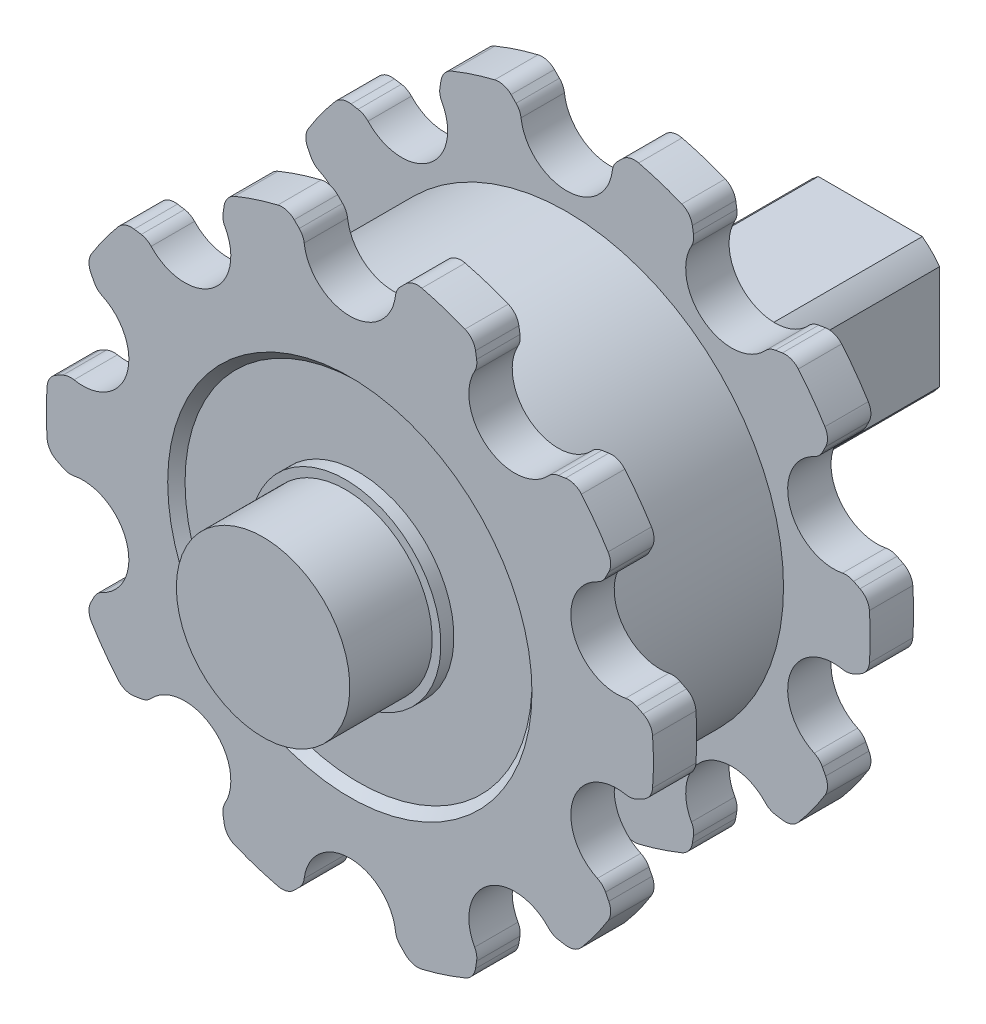
SolidWorks part; units mm, degrees
material "ABS"
ref_plane "Piano frontale" through (0, 0, 0) normal (0, 0, 1) x (1, 0, 0)
ref_plane "Piano superiore" through (0, 0, 0) normal (0, 1, 0) x (1, 0, 0)
ref_plane "Piano destro" through (0, 0, 0) normal (1, 0, 0) x (0, 0, -1)
sketch "Schizzo1" plane through (0, 0, 0) normal (0, 1, 0) x (1, 0, 0)
  line L0 (0, 0) -> (10, 0)
  line L1 (10, 0) -> (10, 9.5)
  line L2 (10, 9.5) -> (11, 9.5)
  line L3 (11, 9.5) -> (11, 11)
  line L4 (11, 11) -> (20, 11)
  line L5 (20, 11) -> (21, 10)
  line L6 (21, 10) -> (35, 10)
  line L7 (35, 10) -> (35, 15)
  line L8 (35, 15) -> (25, 15)
  line L9 (25, 15) -> (25, 35)
  line L10 (25, 35) -> (35, 35)
  line L11 (35, 35) -> (35, 40)
  line L12 (35, 40) -> (21, 40)
  line L13 (21, 40) -> (20, 39)
  line L14 (20, 39) -> (11, 39)
  line L15 (11, 39) -> (11, 40.5)
  line L16 (11, 40.5) -> (10, 40.5)
  line L17 (10, 40.5) -> (10, 70)
  line L20 (10, 70) -> (0, 70)
  line L21 (0, 70) -> (0, 0)
  dimension "D1" = 9.5
  dimension "D2" = 1
  dimension "D3" = 1.5
  dimension "D4" = 9
  dimension "D5" = 1
  dimension "D6" = 1
  dimension "D7" = 14
  dimension "D8" = 5
  dimension "D9" = 20
  dimension "D10" = 10
  dimension "D11" = 15
  dimension "D12" = 29.5
revolve "Rivoluzione1" add sketch "Schizzo1" angle 360 about L21
sketch "Schizzo2" plane through (0, 0, -70) normal (0, 0, -1) x (-1, 0, 0)
  line L0 (-8, -6) -> (-8, 6)
  line L1 (8, -6) -> (8, 6)
  line L2 (-6, 8) -> (6, 8)
  line L3 (-6, -8) -> (6, -8)
  arc A0 (6, 8) -> (-6, 8) centre (0, 0) ccw
  arc A1 (8, -6) -> (8, 6) centre (0, 0) ccw
  arc A2 (-8, 6) -> (-8, -6) centre (0, 0) ccw
  arc A3 (-6, -8) -> (6, -8) centre (0, 0) ccw
  dimension "D2" = 20
  dimension "D1" = 12
extrude "Taglio-Estrusione1" cut sketch "Schizzo2" against normal blind 20
sketch "Schizzo3" plane through (0, 0, -40) normal (0, 0, -1) x (-1, 0, 0)
  line L0 (0, 32.3607) -> (0, 27.0607) construction
  line L1 (0, 27.0607) -> (0, 0) construction
  line L2 (-5.8323, 32.893) -> (-6.4121, 33.4727)
  line L3 (-5.3, 32.3607) -> (0, 32.3607) construction
  line L4 (5.8323, 32.893) -> (6.4121, 33.4727)
  line L5 (0, 32.3607) -> (5.3, 32.3607) construction
  line L6 (14.6156, 30.0391) -> (14.4873, 30.8489)
  line L7 (24.0525, 23.1828) -> (24.8623, 23.3111)
  line L8 (19.0211, 26.1803) -> (15.9059, 21.8925) construction
  line L9 (15.9059, 21.8925) -> (0, 0) construction
  line L10 (14.7333, 29.2956) -> (19.0211, 26.1803) construction
  line L11 (19.0211, 26.1803) -> (23.3089, 23.0651) construction
  line L12 (29.4808, 15.7114) -> (29.853, 16.4419)
  line L13 (33.0854, 4.6176) -> (33.8159, 4.2454)
  line L14 (30.7768, 10) -> (25.7362, 8.3622) construction
  line L15 (25.7362, 8.3622) -> (0, 0) construction
  line L16 (29.139, 15.0406) -> (30.7768, 10) construction
  line L17 (30.7768, 10) -> (32.4146, 4.9594) construction
  line L18 (33.0854, -4.6176) -> (33.8159, -4.2454)
  line L19 (29.4808, -15.7114) -> (29.853, -16.4419)
  line L20 (30.7768, -10) -> (25.7362, -8.3622) construction
  line L21 (25.7362, -8.3622) -> (0, 0) construction
  line L22 (32.4146, -4.9594) -> (30.7768, -10) construction
  line L23 (30.7768, -10) -> (29.139, -15.0406) construction
  line L24 (24.0525, -23.1828) -> (24.8623, -23.3111)
  line L25 (14.6156, -30.0391) -> (14.4873, -30.8489)
  line L26 (19.0211, -26.1803) -> (15.9059, -21.8925) construction
  line L27 (15.9059, -21.8925) -> (0, 0) construction
  line L28 (23.3089, -23.0651) -> (19.0211, -26.1803) construction
  line L29 (19.0211, -26.1803) -> (14.7333, -29.2956) construction
  line L30 (5.8323, -32.893) -> (6.4121, -33.4727)
  line L31 (-5.8323, -32.893) -> (-6.4121, -33.4727)
  line L32 (0, -32.3607) -> (0, -27.0607) construction
  line L33 (0, -27.0607) -> (0, 0) construction
  line L34 (5.3, -32.3607) -> (0, -32.3607) construction
  line L35 (0, -32.3607) -> (-5.3, -32.3607) construction
  line L36 (-14.6156, -30.0391) -> (-14.4873, -30.8489)
  line L37 (-24.0525, -23.1828) -> (-24.8623, -23.3111)
  line L38 (-19.0211, -26.1803) -> (-15.9059, -21.8925) construction
  line L39 (-15.9059, -21.8925) -> (0, 0) construction
  line L40 (-14.7333, -29.2956) -> (-19.0211, -26.1803) construction
  line L41 (-19.0211, -26.1803) -> (-23.3089, -23.0651) construction
  line L42 (-29.4808, -15.7114) -> (-29.853, -16.4419)
  line L43 (-33.0854, -4.6176) -> (-33.8159, -4.2454)
  line L44 (-30.7768, -10) -> (-25.7362, -8.3622) construction
  line L45 (-25.7362, -8.3622) -> (0, 0) construction
  line L46 (-29.139, -15.0406) -> (-30.7768, -10) construction
  line L47 (-30.7768, -10) -> (-32.4146, -4.9594) construction
  line L48 (-33.0854, 4.6176) -> (-33.8159, 4.2454)
  line L49 (-29.4808, 15.7114) -> (-29.853, 16.4419)
  line L50 (-30.7768, 10) -> (-25.7362, 8.3622) construction
  line L51 (-25.7362, 8.3622) -> (0, 0) construction
  line L52 (-32.4146, 4.9594) -> (-30.7768, 10) construction
  line L53 (-30.7768, 10) -> (-29.139, 15.0406) construction
  line L54 (-24.0525, 23.1828) -> (-24.8623, 23.3111)
  line L55 (-14.6156, 30.0391) -> (-14.4873, 30.8489)
  line L56 (-19.0211, 26.1803) -> (-15.9059, 21.8925) construction
  line L57 (-15.9059, 21.8925) -> (0, 0) construction
  line L58 (-23.3089, 23.0651) -> (-19.0211, 26.1803) construction
  line L59 (-19.0211, 26.1803) -> (-14.7333, 29.2956) construction
  arc A1 (-5.2612, 31.7204) -> (5.2612, 31.7204) centre (0, 32.3607) ccw
  arc A3 (14.3884, 28.7548) -> (22.9012, 22.5699) centre (19.0211, 26.1803) ccw
  arc A4 (-5.2612, 31.7204) -> (-5.8323, 32.893) centre (-7.2465, 31.4788) ccw
  arc A5 (-6.4121, 33.4727) -> (-8.3006, 34.0015) centre (-7.8263, 32.0585) ccw
  arc A6 (5.8323, 32.893) -> (5.2612, 31.7204) centre (7.2465, 31.4788) ccw
  arc A7 (8.3006, 34.0015) -> (6.4121, 33.4727) centre (7.8263, 32.0585) ccw
  arc A8 (8.3006, 34.0015) -> (-8.3006, 34.0015) centre (0, 0) ccw
  circle A9 centre (0, 0) radius 35 construction
  arc A10 (14.3884, 28.7548) -> (14.6156, 30.0391) centre (12.6402, 29.7263) ccw
  arc A11 (14.4873, 30.8489) -> (13.2702, 32.3867) centre (12.5119, 30.5361) ccw
  arc A12 (24.0525, 23.1828) -> (22.9012, 22.5699) centre (24.3653, 21.2075) ccw
  arc A13 (26.7009, 22.6288) -> (24.8623, 23.3111) centre (25.1751, 21.3357) ccw
  arc A14 (26.7009, 22.6288) -> (13.2702, 32.3867) centre (0, 0) ccw
  arc A15 (28.5421, 14.8058) -> (31.7937, 4.7985) centre (30.7768, 10) ccw
  arc A16 (28.5421, 14.8058) -> (29.4808, 15.7114) centre (27.6988, 16.6193) ccw
  arc A17 (29.853, 16.4419) -> (29.7723, 18.4014) centre (28.071, 17.3499) ccw
  arc A18 (33.0854, 4.6176) -> (31.7937, 4.7985) centre (32.1774, 2.8356) ccw
  arc A19 (34.9023, 2.6127) -> (33.8159, 4.2454) centre (32.9079, 2.4634) ccw
  arc A20 (34.9023, 2.6127) -> (29.7723, 18.4014) centre (0, 0) ccw
  arc A21 (31.7937, -4.7985) -> (28.5421, -14.8058) centre (30.7768, -10) ccw
  arc A22 (31.7937, -4.7985) -> (33.0854, -4.6176) centre (32.1774, -2.8356) ccw
  arc A23 (33.8159, -4.2454) -> (34.9023, -2.6127) centre (32.9079, -2.4634) ccw
  arc A24 (29.4808, -15.7114) -> (28.5421, -14.8058) centre (27.6988, -16.6193) ccw
  arc A25 (29.7723, -18.4014) -> (29.853, -16.4419) centre (28.071, -17.3499) ccw
  arc A26 (29.7723, -18.4014) -> (34.9023, -2.6127) centre (0, 0) ccw
  arc A27 (22.9012, -22.5699) -> (14.3884, -28.7548) centre (19.0211, -26.1803) ccw
  arc A28 (22.9012, -22.5699) -> (24.0525, -23.1828) centre (24.3653, -21.2075) ccw
  arc A29 (24.8623, -23.3111) -> (26.7009, -22.6288) centre (25.1751, -21.3357) ccw
  arc A30 (14.6156, -30.0391) -> (14.3884, -28.7548) centre (12.6402, -29.7263) ccw
  arc A31 (13.2702, -32.3867) -> (14.4873, -30.8489) centre (12.5119, -30.5361) ccw
  arc A32 (13.2702, -32.3867) -> (26.7009, -22.6288) centre (0, 0) ccw
  arc A33 (5.2612, -31.7204) -> (-5.2612, -31.7204) centre (0, -32.3607) ccw
  arc A34 (5.2612, -31.7204) -> (5.8323, -32.893) centre (7.2465, -31.4788) ccw
  arc A35 (6.4121, -33.4727) -> (8.3006, -34.0015) centre (7.8263, -32.0585) ccw
  arc A36 (-5.8323, -32.893) -> (-5.2612, -31.7204) centre (-7.2465, -31.4788) ccw
  arc A37 (-8.3006, -34.0015) -> (-6.4121, -33.4727) centre (-7.8263, -32.0585) ccw
  arc A38 (-8.3006, -34.0015) -> (8.3006, -34.0015) centre (0, 0) ccw
  arc A39 (-14.3884, -28.7548) -> (-22.9012, -22.5699) centre (-19.0211, -26.1803) ccw
  arc A40 (-14.3884, -28.7548) -> (-14.6156, -30.0391) centre (-12.6402, -29.7263) ccw
  arc A41 (-14.4873, -30.8489) -> (-13.2702, -32.3867) centre (-12.5119, -30.5361) ccw
  arc A42 (-24.0525, -23.1828) -> (-22.9012, -22.5699) centre (-24.3653, -21.2075) ccw
  arc A43 (-26.7009, -22.6288) -> (-24.8623, -23.3111) centre (-25.1751, -21.3357) ccw
  arc A44 (-26.7009, -22.6288) -> (-13.2702, -32.3867) centre (0, 0) ccw
  arc A45 (-28.5421, -14.8058) -> (-31.7937, -4.7985) centre (-30.7768, -10) ccw
  arc A46 (-28.5421, -14.8058) -> (-29.4808, -15.7114) centre (-27.6988, -16.6193) ccw
  arc A47 (-29.853, -16.4419) -> (-29.7723, -18.4014) centre (-28.071, -17.3499) ccw
  arc A48 (-33.0854, -4.6176) -> (-31.7937, -4.7985) centre (-32.1774, -2.8356) ccw
  arc A49 (-34.9023, -2.6127) -> (-33.8159, -4.2454) centre (-32.9079, -2.4634) ccw
  arc A50 (-34.9023, -2.6127) -> (-29.7723, -18.4014) centre (0, 0) ccw
  arc A51 (-31.7937, 4.7985) -> (-28.5421, 14.8058) centre (-30.7768, 10) ccw
  arc A52 (-31.7937, 4.7985) -> (-33.0854, 4.6176) centre (-32.1774, 2.8356) ccw
  arc A53 (-33.8159, 4.2454) -> (-34.9023, 2.6127) centre (-32.9079, 2.4634) ccw
  arc A54 (-29.4808, 15.7114) -> (-28.5421, 14.8058) centre (-27.6988, 16.6193) ccw
  arc A55 (-29.7723, 18.4014) -> (-29.853, 16.4419) centre (-28.071, 17.3499) ccw
  arc A56 (-29.7723, 18.4014) -> (-34.9023, 2.6127) centre (0, 0) ccw
  arc A57 (-22.9012, 22.5699) -> (-14.3884, 28.7548) centre (-19.0211, 26.1803) ccw
  arc A58 (-22.9012, 22.5699) -> (-24.0525, 23.1828) centre (-24.3653, 21.2075) ccw
  arc A59 (-24.8623, 23.3111) -> (-26.7009, 22.6288) centre (-25.1751, 21.3357) ccw
  arc A60 (-14.6156, 30.0391) -> (-14.3884, 28.7548) centre (-12.6402, 29.7263) ccw
  arc A61 (-13.2702, 32.3867) -> (-14.4873, 30.8489) centre (-12.5119, 30.5361) ccw
  arc A62 (-13.2702, 32.3867) -> (-26.7009, 22.6288) centre (0, 0) ccw
  point P167 (0, 0)
  dimension "D1" = 10.6
  dimension "D5" = 2
  dimension "D6" = 2
  dimension "D7" = 2
  dimension "D8" = 2
  dimension "D2" = 45
  dimension "D3" = 27.0607
  dimension "D4" = 45
  dimension "D9" = 10
extrude "Taglio-Estrusione2" cut sketch "Schizzo3" against normal blind 43
